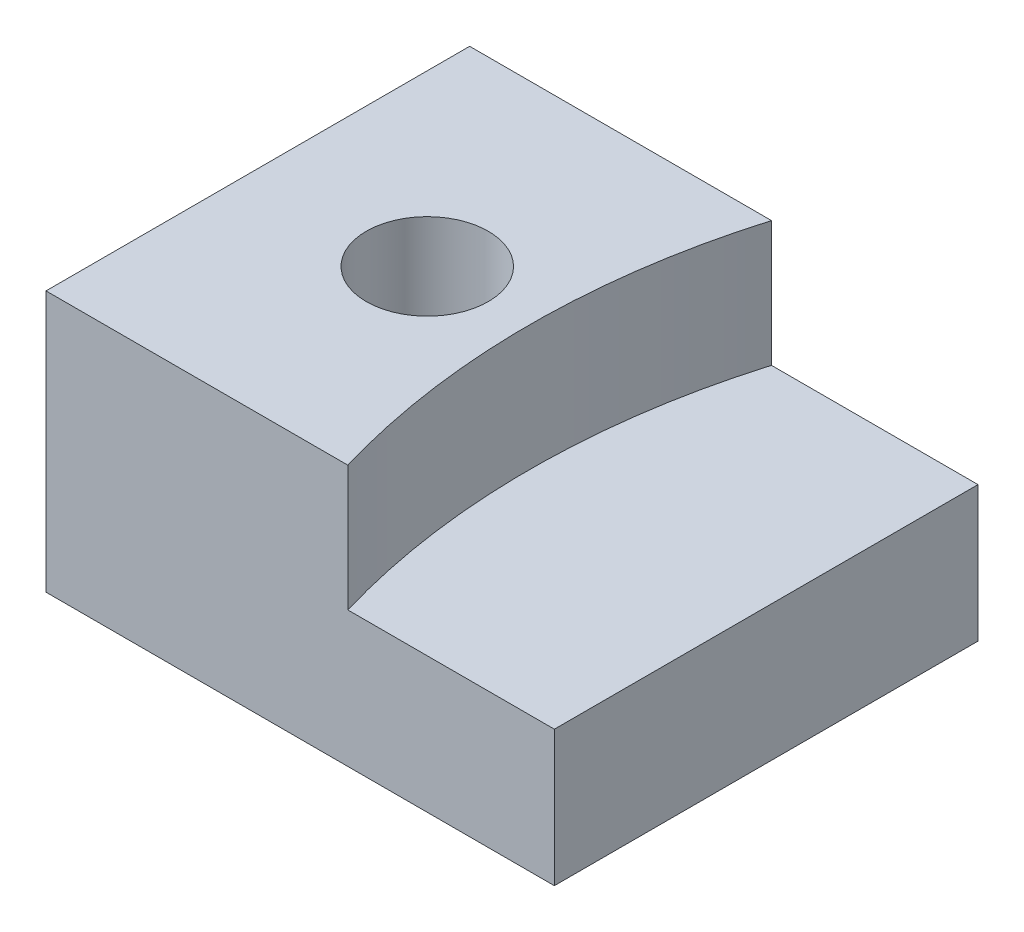
SolidWorks part; units mm, degrees
material "Delrin 2700 NC010, Low Viscosity Acetal Copolymer (SS)"
ref_plane "Front" through (0, 0, 0) normal (0, 0, 1) x (1, 0, 0)
ref_plane "Top" through (0, 0, 0) normal (0, 1, 0) x (1, 0, 0)
ref_plane "Right" through (0, 0, 0) normal (1, 0, 0) x (0, 0, -1)
sketch "Sketch3" plane through (0, 0, 0) normal (0, 1, 0) x (1, 0, 0)
  line L5 (-2.5, -3.125) -> (5, -3.125)
  line L6 (-2.5, -3.125) -> (-2.5, 3.125)
  line L7 (-2.5, 3.125) -> (5, 3.125)
  line L8 (5, -3.125) -> (5, 3.125)
  circle A0 centre (0, 0) radius 0.9
  point P9 (-2.5, 0)
  dimension "D1" = 1.8
  dimension "D2" = 6.25
  dimension "D3" = 2.5
  dimension "D4" = 7.5
extrude "Boss-Extrude1" add sketch "Sketch3" along normal blind 2
sketch "Sketch6" plane through (0, 2, 0) normal (0, 1, 0) x (1, 0, 0)
  line L0 (-2.5, 3.125) -> (-2.5, -3.125) construction
  line L1 (-2.5, 3.125) -> (-2.5, -3.125)
  line L2 (-2.5, 3.125) -> (1.9532, 3.125)
  line L3 (5, 3.125) -> (-2.5, 3.125) construction
  line L4 (1.9532, 3.125) -> (1.9532, -3.125) construction
  line L5 (-2.5, -3.125) -> (5, -3.125) construction
  line L6 (1.9532, -3.125) -> (-2.5, -3.125)
  circle A0 centre (0, 0) radius 0.9 construction
  circle A1 centre (0, 0) radius 0.9
  arc A2 (1.9532, -3.125) -> (1.9532, 3.125) centre (12.5, 0) cw
  point P12 (1.5, 0)
  dimension "D1" = 11
  dimension "D2" = 1.5
extrude "Boss-Extrude3" add sketch "Sketch6" along normal blind 1.85
